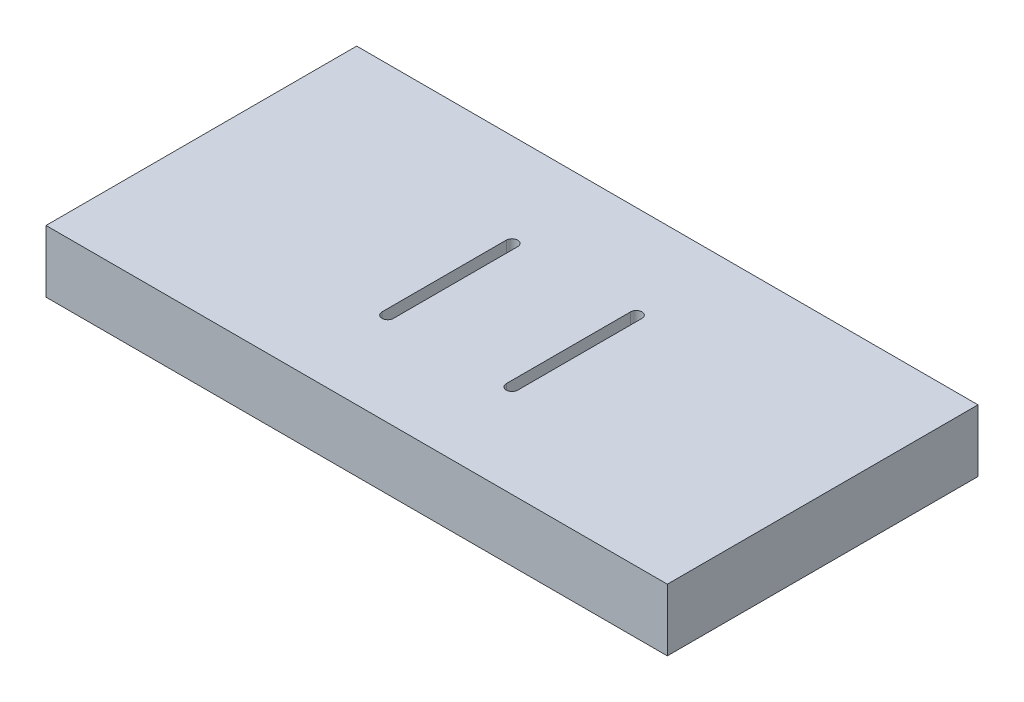
SolidWorks part; units mm, degrees
material "Acrylic (Medium-high impact)"
ref_plane "Front Plane" through (0, 0, 0) normal (0, 0, 1) x (1, 0, 0)
ref_plane "Top Plane" through (0, 0, 0) normal (0, 1, 0) x (1, 0, 0)
ref_plane "Right Plane" through (0, 0, 0) normal (1, 0, 0) x (0, 0, -1)
sketch "Sketch1" plane through (0, 0, 0) normal (0, 1, 0) x (1, 0, 0)
  line L1 (-150, -75) -> (150, -75)
  line L2 (-150, -75) -> (-150, 75)
  line L3 (-150, 75) -> (150, 75)
  line L4 (150, -75) -> (150, 75)
  line L5 (-150, -75) -> (150, 75) construction
  line L6 (-150, 75) -> (150, -75) construction
  point P0 (0, 0)
  dimension "D1" = 300
  dimension "D2" = 150
extrude "Boss-Extrude1" add sketch "Sketch1" along normal blind 30
sketch "Sketch4" plane through (0, 30, 0) normal (0, 1, 0) x (1, 0, 0)
  line L0 (-30, -30) -> (-30, 30) construction
  line L1 (-32.75, -30) -> (-32.75, 30)
  line L2 (-27.25, -30) -> (-27.25, 30)
  line L3 (0, -11) -> (0, 11) construction
  line L4 (30, -30) -> (30, 30) construction
  line L5 (32.75, -30) -> (32.75, 30)
  line L6 (27.25, -30) -> (27.25, 30)
  arc A0 (-32.75, -30) -> (-27.25, -30) centre (-30, -30) ccw
  arc A1 (-27.25, 30) -> (-32.75, 30) centre (-30, 30) ccw
  arc A2 (32.75, -30) -> (27.25, -30) centre (30, -30) cw
  arc A3 (27.25, 30) -> (32.75, 30) centre (30, 30) cw
  point P2 (-30, 0)
  point P14 (30, 0)
  dimension "D1" = 5.5
  dimension "D2" = 60
  dimension "D3" = 30
extrude "Cut-Extrude2" cut sketch "Sketch4" against normal blind 30
ref_plane "Plane1" through (-30, 0, 0) normal (1, 0, 0) x (0, 0, -1)
hole_wizard "CBORE for M5 Pan Head Machine Screw1" positions "Sketch6" profile "Sketch7" counterbore size "M5" standard "ANSI Metric"
sketch "Sketch6" plane through (0, 0, 0) normal (0, -1, 0) x (-1, 0, 0)
  point P0 (30, -30)
  point P4 (-30, -30)
sketch "Sketch7" plane through (-30, 0, 30) normal (1, 0, 0) x (0, 0, -1)
  line L0 (0, 0) -> (0, 110)
  line L1 (0, 110) -> (2.75, 110)
  line L2 (2.75, 110) -> (2.75, 3.7)
  line L3 (2.75, 3.7) -> (5.5, 3.7)
  line L4 (5.5, 3.7) -> (5.5, 0)
  line L5 (5.5, 0) -> (0, 0)
  line L10 (0, 110) -> (-2.75, 110) construction
  line L11 (0, -6.35) -> (0, 107.95) construction
  dimension "Hole Dia." = 5.5
  dimension "Hole Depth" = 110
  dimension "C'Bore Dia." = 11
  dimension "C'Bore Depth" = 3.7
  dimension "Drill Angle" = 180
sketch "Sketch8" plane through (0, 0, 0) normal (0, -1, 0) x (1, 0, 0)
  line L0 (-30, 30) -> (-30, -30) construction
  line L1 (-24.5, 30) -> (-24.5, -30)
  line L2 (-35.5, 30) -> (-35.5, -30)
  line L3 (0, -11) -> (0, 11) construction
  line L4 (30, 30) -> (30, -30) construction
  line L5 (24.5, 30) -> (24.5, -30)
  line L6 (35.5, 30) -> (35.5, -30)
  arc A0 (-24.5, 30) -> (-35.5, 30) centre (-30, 30) ccw
  arc A1 (-35.5, -30) -> (-24.5, -30) centre (-30, -30) ccw
  arc A2 (24.5, 30) -> (35.5, 30) centre (30, 30) cw
  arc A3 (35.5, -30) -> (24.5, -30) centre (30, -30) cw
  point P4 (-30, 0)
  point P13 (30, 0)
  dimension "D1" = 5.5
extrude "Cut-Extrude3" cut sketch "Sketch8" against normal blind 10
equation "\"BaseL\"= 30cm"
equation "\"BaseW\"= 15cm"
equation "\"BaseH\"= 3cm"
equation "\"D1@Sketch1\"=\"BaseL\""
equation "\"D2@Sketch1\"=\"BaseW\""
equation "\"D1@Boss-Extrude1\"=\"BaseH\""
equation "\"Clearance\"= 1mm"
equation "\"SupportW\"= 1.5cm"
equation "\"Separation\"= 10cm"
